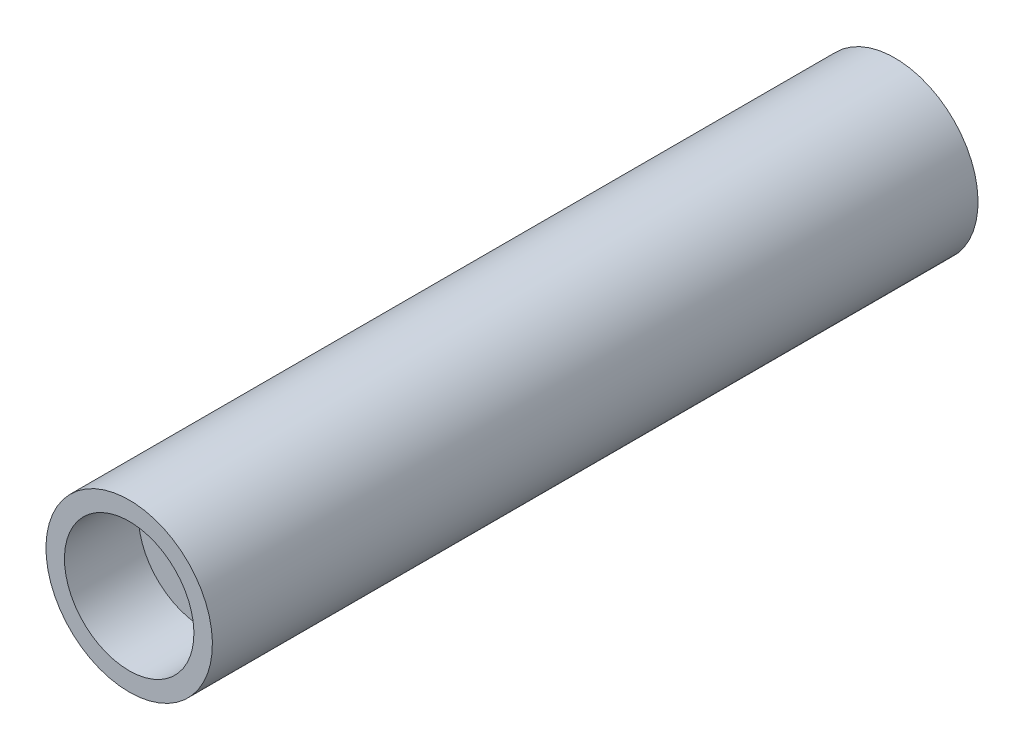
SolidWorks part; units mm, degrees
material "Brass"
ref_plane "Front Plane" through (0, 0, 0) normal (0, 0, 1) x (1, 0, 0)
ref_plane "Top Plane" through (0, 0, 0) normal (0, 1, 0) x (1, 0, 0)
ref_plane "Right Plane" through (0, 0, 0) normal (1, 0, 0) x (0, 0, -1)
sketch "Sketch1" plane through (0, 0, 0) normal (1, 0, 0) x (0, 0, -1)
  line L0 (-16.93, 0) -> (16.93, 0) construction
  line L1 (0, 2.082) -> (0, -2.082) construction
  line L2 (16.7, 3.5) -> (20.7, 3.5)
  line L3 (-20.7, 4.5) -> (20.7, 4.5)
  line L4 (-20.7, 4.5) -> (-20.7, 3.5)
  line L5 (-20.7, 3.5) -> (-16.7, 3.5)
  line L6 (20.7, 4.5) -> (20.7, 3.5)
  line L7 (-20.7, 4.5) -> (20.7, 3.5) construction
  line L8 (-20.7, 3.5) -> (20.7, 4.5) construction
  line L9 (-16.7, 3.5) -> (-16.7, 2)
  line L10 (-16.7, 2) -> (16.7, 2)
  line L11 (16.7, 3.5) -> (16.7, 2)
  point P0 (0, 4)
  point P3 (0, 0)
  point P6 (0, 0)
  point P15 (20.7, 4)
  dimension "D1" = 41.4
  dimension "D2" = 4
  dimension "D3" = 4
  dimension "D4" = 7
  dimension "D5" = 2
  dimension "D6" = 4.5
revolve "Revolve1" add sketch "Sketch1" angle 360 about L0
